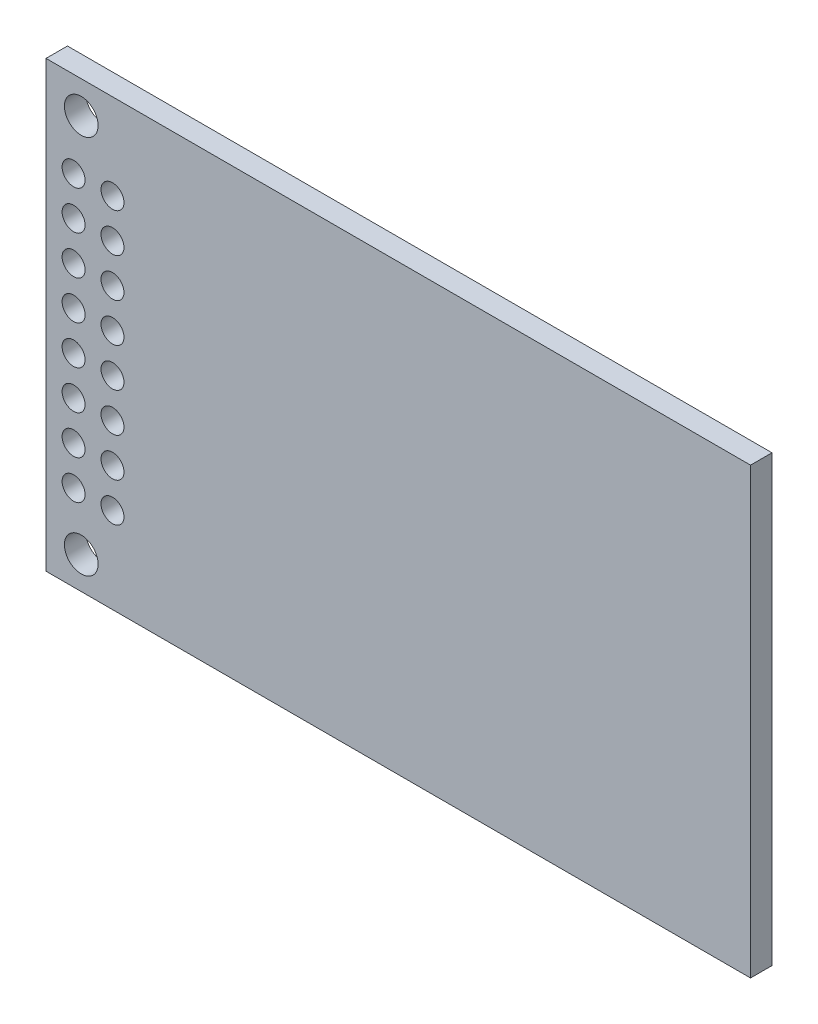
SolidWorks part; units mm, degrees
material "ABS"
ref_plane "Plano frontal" through (0, 0, 0) normal (0, 0, 1) x (1, 0, 0)
ref_plane "Plano superior" through (0, 0, 0) normal (0, 1, 0) x (1, 0, 0)
ref_plane "Plano direito" through (0, 0, 0) normal (1, 0, 0) x (0, 0, -1)
sketch "Esboço1" plane through (0, 0, 0) normal (0, 0, 1) x (1, 0, 0)
  line L1 (-23, -14.5) -> (23, -14.5)
  line L2 (-23, -14.5) -> (-23, 14.5)
  line L3 (-23, 14.5) -> (23, 14.5)
  line L4 (23, -14.5) -> (23, 14.5)
  line L5 (-23, -14.5) -> (23, 14.5) construction
  line L6 (-23, 14.5) -> (23, -14.5) construction
  point P0 (0, 0)
  dimension "D1" = 46
  dimension "D2" = 29
extrude "Ressalto-extrusão1" add sketch "Esboço1" along normal blind 1.4
sketch "Esboço2" plane through (0, 0, 1.4) normal (0, 0, 1) x (1, 0, 0)
  line L0 (23, 14.5) -> (-23, 14.5) construction
  line L1 (-23, 14.5) -> (-23, -14.5) construction
  line L2 (-23, 0) -> (23, 0) construction
  line L4 (-23, -14.5) -> (23, -14.5) construction
  circle A0 centre (-20.7, 12.4) radius 1.1
  circle A1 centre (-20.7, -12.4) radius 1.1
  circle A2 centre (-21.2, 8.89) radius 0.75
  circle A3 centre (-18.66, 8.89) radius 0.75
  circle A4 centre (-18.66, 6.35) radius 0.75
  circle A5 centre (-18.66, 3.81) radius 0.75
  circle A6 centre (-18.66, 1.27) radius 0.75
  circle A7 centre (-18.66, -1.27) radius 0.75
  circle A8 centre (-18.66, -3.81) radius 0.75
  circle A9 centre (-18.66, -6.35) radius 0.75
  circle A10 centre (-18.66, -8.89) radius 0.75
  circle A11 centre (-21.2, 6.35) radius 0.75
  circle A12 centre (-21.2, 3.81) radius 0.75
  circle A13 centre (-21.2, 1.27) radius 0.75
  circle A14 centre (-21.2, -1.27) radius 0.75
  circle A15 centre (-21.2, -3.81) radius 0.75
  circle A16 centre (-21.2, -6.35) radius 0.75
  circle A17 centre (-21.2, -8.89) radius 0.75
  dimension "D3" = 2.2
  dimension "D4" = 1.5
  dimension "D1" = 2.1
  dimension "D2" = 2.3
  dimension "D7" = 2.54
  dimension "D8" = 2.54
  dimension "D9" = 1.8
  dimension "D5" = 2
  dimension "D6" = 8
extrude "Corte-extrusão1" cut sketch "Esboço2" against normal through all
